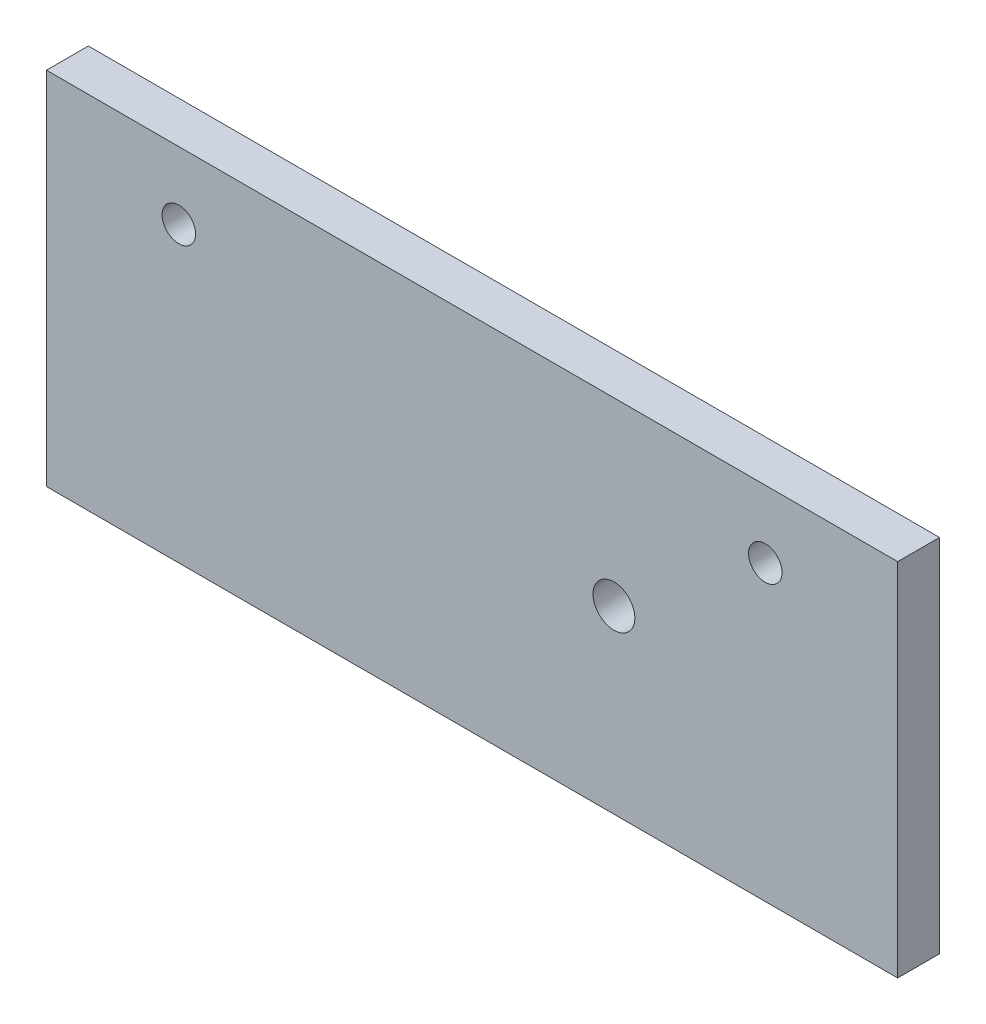
SolidWorks part; units mm, degrees
ref_plane "Front Plane" through (0, 0, 0) normal (0, 0, 1) x (1, 0, 0)
ref_plane "Top Plane" through (0, 0, 0) normal (0, 1, 0) x (1, 0, 0)
ref_plane "Right Plane" through (0, 0, 0) normal (1, 0, 0) x (0, 0, -1)
sketch "Sketch1" plane through (0, 0, 0) normal (0, 0, 1) x (1, 0, 0)
  line L1 (-50.8, 21.52) -> (50.8, 21.52)
  line L2 (-50.8, 21.52) -> (-50.8, -21.52)
  line L3 (-50.8, -21.52) -> (50.8, -21.52)
  line L4 (50.8, 21.52) -> (50.8, -21.52)
  line L5 (-50.8, 21.52) -> (50.8, -21.52) construction
  line L6 (-50.8, -21.52) -> (50.8, 21.52) construction
  point P0 (0, 0)
  dimension "D1" = 43.04
  dimension "D2" = 101.6
extrude "Boss-Extrude1" add sketch "Sketch1" along normal blind 5
sketch "Sketch2" plane through (0, 0, 5) normal (0, 0, 1) x (1, 0, 0)
  line L0 (0, 21.52) -> (0, -21.52) construction
  line L1 (50.8, 21.52) -> (-50.8, 21.52) construction
  line L2 (-50.8, -21.52) -> (50.8, -21.52) construction
  line L3 (-50.8, 0) -> (50.8, 0) construction
  line L4 (-50.8, 21.52) -> (-50.8, -21.52) construction
  line L5 (50.8, -21.52) -> (50.8, 21.52) construction
  circle A0 centre (16.9333, 0) radius 2.5
  dimension "D1" = 5
  dimension "D2" = 67.7333
extrude "Cut-Extrude1" cut sketch "Sketch2" against normal through all
sketch "Sketch3" plane through (0, 0, 5) normal (0, 0, 1) x (1, 0, 0)
  line L0 (0, 21.52) -> (0, -21.52) construction
  line L1 (50.8, 21.52) -> (-50.8, 21.52) construction
  line L2 (-50.8, -21.52) -> (50.8, -21.52) construction
  line L3 (-50.8, 0) -> (50.8, 0) construction
  line L4 (-50.8, 21.52) -> (-50.8, -21.52) construction
  line L5 (50.8, -21.52) -> (50.8, 21.52) construction
  circle A0 centre (-35, 13.48) radius 2
  circle A1 centre (35, 13.48) radius 2
  dimension "D1" = 4
  dimension "D2" = 4
  dimension "D3" = 70
  dimension "D4" = 15.8
  dimension "D5" = 35
extrude "Cut-Extrude2" cut sketch "Sketch3" against normal through all
